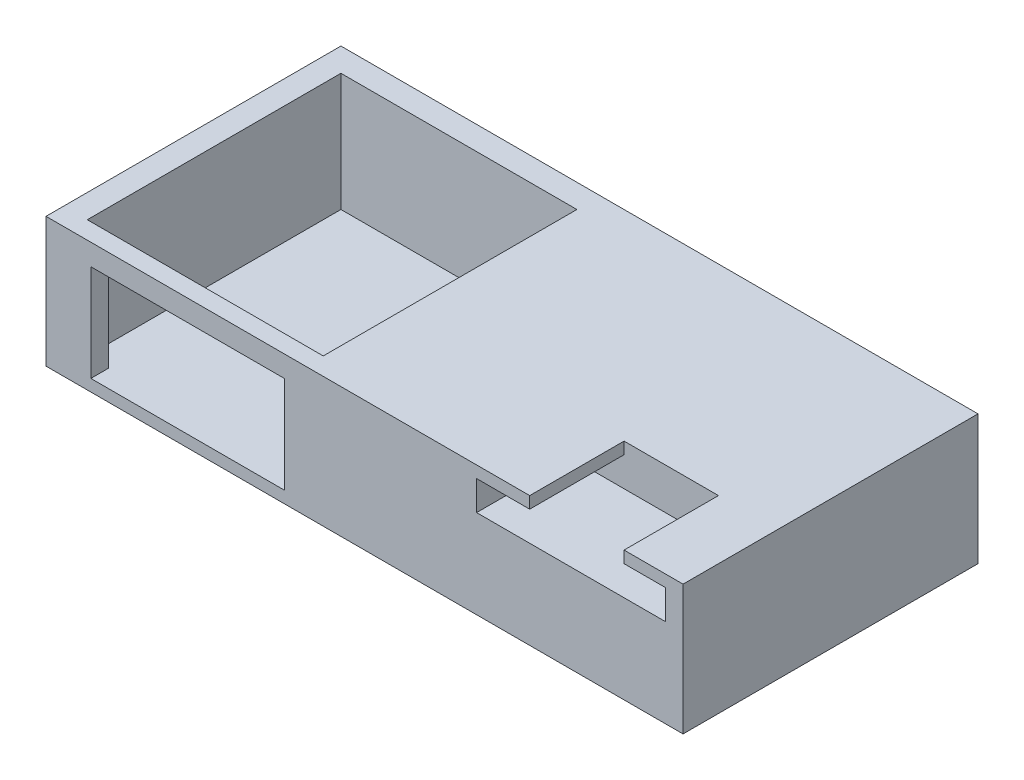
SolidWorks part; units mm, degrees
ref_plane "Front Plane" through (0, 0, 0) normal (0, 0, 1) x (1, 0, 0)
ref_plane "Top Plane" through (0, 0, 0) normal (0, 1, 0) x (1, 0, 0)
ref_plane "Right Plane" through (0, 0, 0) normal (1, 0, 0) x (0, 0, -1)
sketch "Sketch8" plane through (0, 0, 0) normal (0, 1, 0) x (1, 0, 0)
  line L0 (-27.5, 26) -> (-27.5, 0) construction
  line L1 (-27.5, 0) -> (27.5, 0) construction
  line L2 (27.5, 0) -> (27.5, 26) construction
  line L3 (27.5, 26) -> (-27.5, 26) construction
  line L4 (-27, 25.5) -> (-27, 0.5)
  line L5 (-27, 0.5) -> (27, 0.5)
  line L6 (27, 0.5) -> (27, 25.5)
  line L7 (27, 25.5) -> (-27, 25.5)
  point P4 (0, 0)
  dimension "D2" = 54
  dimension "D3" = 25
  dimension "D1" = 0.5
extrude "Boss-Extrude1" add sketch "Sketch8" along normal blind 11
sketch "Sketch9" plane through (0, 11, 0) normal (0, 1, 0) x (1, 0, 0)
  line L0 (27, 25.5) -> (-27, 25.5) construction
  line L1 (-25, 23.5) -> (-5, 23.5)
  line L2 (-25, 23.5) -> (-25, 2)
  line L3 (-25, 2) -> (-5, 2)
  line L4 (-5, 23.5) -> (-5, 2)
  line L5 (-27, 25.5) -> (-27, 0.5) construction
  line L7 (11.5, 9.5) -> (19, 9.5)
  line L8 (11.5, 9.5) -> (11.5, 2)
  line L9 (11.5, 2) -> (19, 2)
  line L10 (19, 9.5) -> (19, 2)
  dimension "D1" = 20
  dimension "D2" = 21.5
  dimension "D3" = 2
  dimension "D4" = 2
  dimension "D5" = 16.5
  dimension "7.5" = 7.5
extrude "Cut-Extrude1" cut sketch "Sketch9" against normal blind 10 contours L4 L1 L2 L3
sketch "Sketch11" plane through (0, 11, 0) normal (0, 1, 0) x (1, 0, 0)
  line L2 (-27, 0.5) -> (27, 0.5) construction
  line L8 (22, 8.5) -> (14, 8.5)
  line L9 (22, 0.5) -> (22, 8.5)
  line L10 (14, 0.5) -> (22, 0.5)
  line L11 (14, 8.5) -> (14, 0.5)
  line L12 (-5, 23.5) -> (-25, 23.5)
  line L13 (-5, 2) -> (-5, 23.5)
  line L14 (-25, 2) -> (-5, 2)
  line L15 (-25, 23.5) -> (-25, 2)
  line L16 (-5, 23.5) -> (-25, 23.5)
  line L17 (-5, 2) -> (-5, 23.5)
  line L18 (-25, 2) -> (-5, 2)
  line L19 (-25, 23.5) -> (-25, 2)
  dimension "D3" = 8
  dimension "D1" = 8
  dimension "D4" = 19
  dimension "D2" = 0
extrude "Cut-Extrude5" cut sketch "Sketch11" against normal blind 3.5 contours L8 L11 L10 L9
sketch "Sketch10" plane through (0, 0, -0.5) normal (0, 0, 1) x (1, 0, 0)
  line L4 (-25, 11) -> (-5, 11) construction
  line L5 (-5, 11) -> (-5, 1) construction
  line L7 (-25, 1) -> (-25, 11) construction
  line L12 (-25, 11) -> (-5, 11)
  line L13 (-5, 11) -> (-5, 1)
  line L14 (-5, 1) -> (-25, 1)
  line L15 (-25, 1) -> (-25, 11)
  line L16 (-23.2, 9.2) -> (-6.8, 9.2)
  line L17 (-6.8, 9.2) -> (-6.8, 1)
  line L19 (-23.2, 1) -> (-23.2, 9.2)
  line L20 (-6.8, 2.8) -> (-23.2, 2.8) construction
  line L21 (-23.2, 2.8) -> (-23.2, 9.2) construction
  line L22 (-6.8, 9.2) -> (-6.8, 2.8) construction
  dimension "D1" = 1.8
extrude "Joystick Entry" cut sketch "Sketch10" against normal up to next contours L19 L14 L17 L16
sketch "Sketch13" plane through (0, 0, -0.5) normal (0, 0, 1) x (1, 0, 0)
  line L0 (14, 9.25) -> (22, 9.25) construction
  line L1 (14, 7.5) -> (14, 11) construction
  line L2 (22, 7.5) -> (22, 11) construction
  line L3 (18, 9.25) -> (18, 15.6595) construction
  line L4 (9.5, 10) -> (25.5, 10)
  line L5 (9.5, 10) -> (9.5, 7.5)
  line L6 (9.5, 7.5) -> (25.5, 7.5)
  line L7 (25.5, 10) -> (25.5, 7.5)
  line L8 (22, 11) -> (27, 11) construction
  dimension "D1" = 16
  dimension "D2" = 8.5
  dimension "D3" = 1
  dimension "D4" = 3.5
extrude "Cut-Extrude6" cut sketch "Sketch13" against normal up to surface (8 mm away) contours L5 L4 L7 L6 up to face at (18, 9.25, -8.5)
